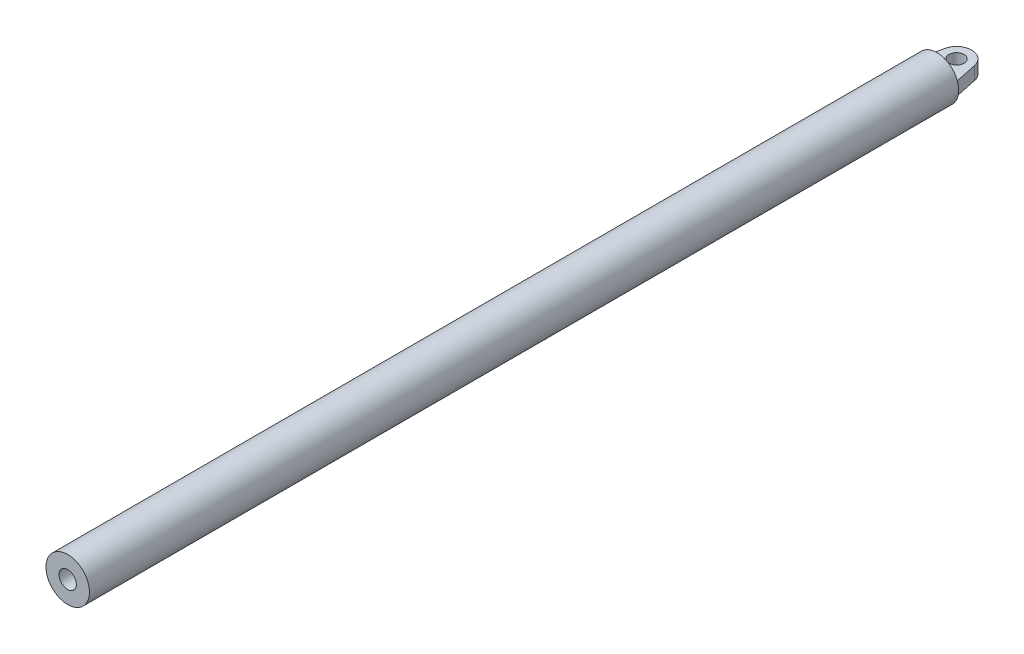
SolidWorks part; units mm, degrees
ref_plane "Front Plane" through (0, 0, 0) normal (0, 0, 1) x (1, 0, 0)
ref_plane "Top Plane" through (0, 0, 0) normal (0, 1, 0) x (1, 0, 0)
ref_plane "Right Plane" through (0, 0, 0) normal (1, 0, 0) x (0, 0, -1)
sketch "Sketch1" plane through (0, 0, 0) normal (0, 0, 1) x (1, 0, 0)
  circle A0 centre (0, 0) radius 50
  dimension "D1" = 100
extrude "Boss-Extrude1" add sketch "Sketch1" along normal blind 2000
shell "Shell1" thickness 30
sketch "Sketch2" plane through (0, 0, 0) normal (0, 1, 0) x (1, 0, 0)
  line L0 (-45, 0) -> (-34.2808, 52.0586)
  line L1 (50, 0) -> (-50, 0) construction
  line L2 (34.2808, 52.0586) -> (45, 0)
  line L3 (-45, 0) -> (45, 0)
  circle A0 centre (0, 45) radius 17.5
  arc A1 (-34.2808, 52.0586) -> (34.2808, 52.0586) centre (0, 45) cw
  dimension "D1" = 35
  dimension "D2" = 35
  dimension "D3" = 45
  dimension "D4" = 45
  dimension "D5" = 45
extrude "Boss-Extrude2" add sketch "Sketch2" along normal mid plane 30
